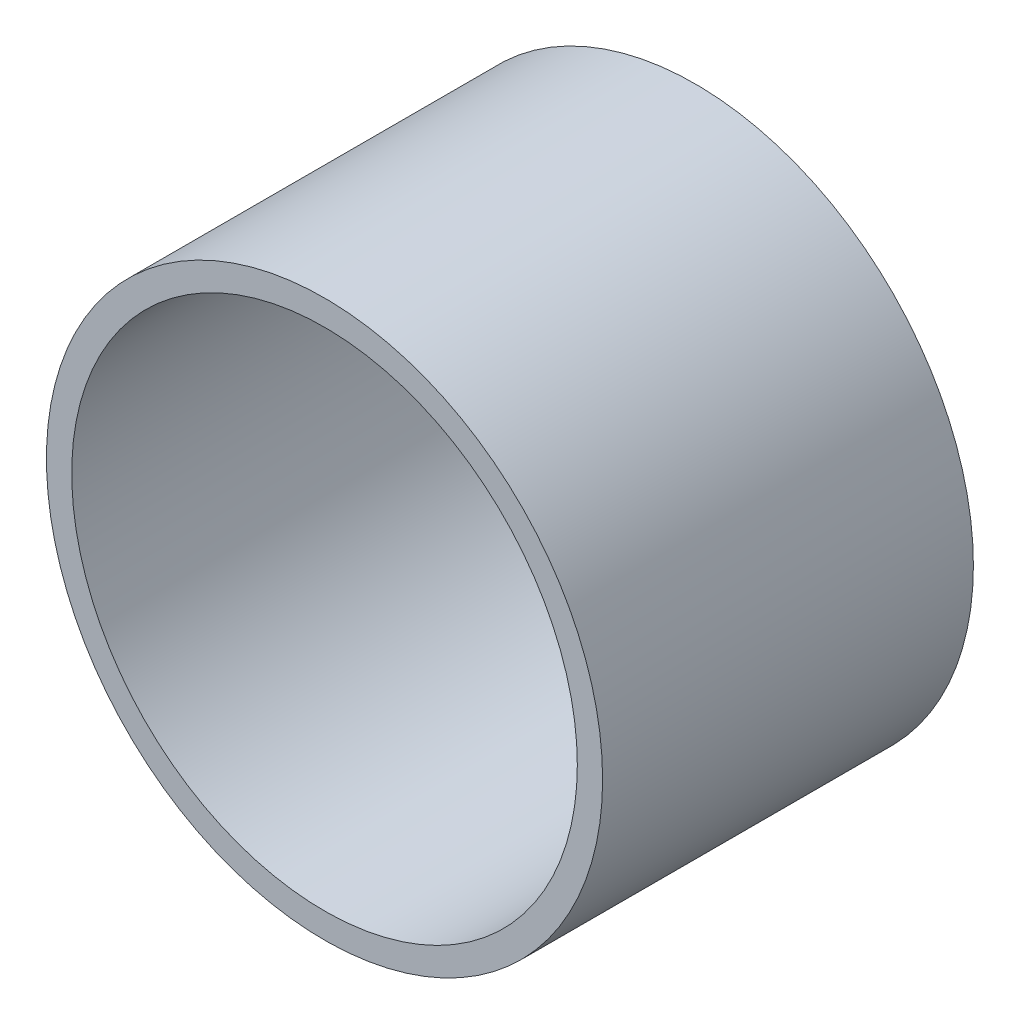
SolidWorks part; units mm, degrees
ref_plane "Front Plane" through (0, 0, 0) normal (0, 0, 1) x (1, 0, 0)
ref_plane "Top Plane" through (0, 0, 0) normal (0, 1, 0) x (1, 0, 0)
ref_plane "Right Plane" through (0, 0, 0) normal (1, 0, 0) x (0, 0, -1)
sketch "Sketch1" plane through (0, 0, 0) normal (0, 0, 1) x (1, 0, 0)
  circle A0 centre (0, 0) radius 16.5
  circle A1 centre (0, 0) radius 15
  dimension "D1" = 33
  dimension "D2" = 30
extrude "Boss-Extrude1" add sketch "Sketch1" along normal blind 22
